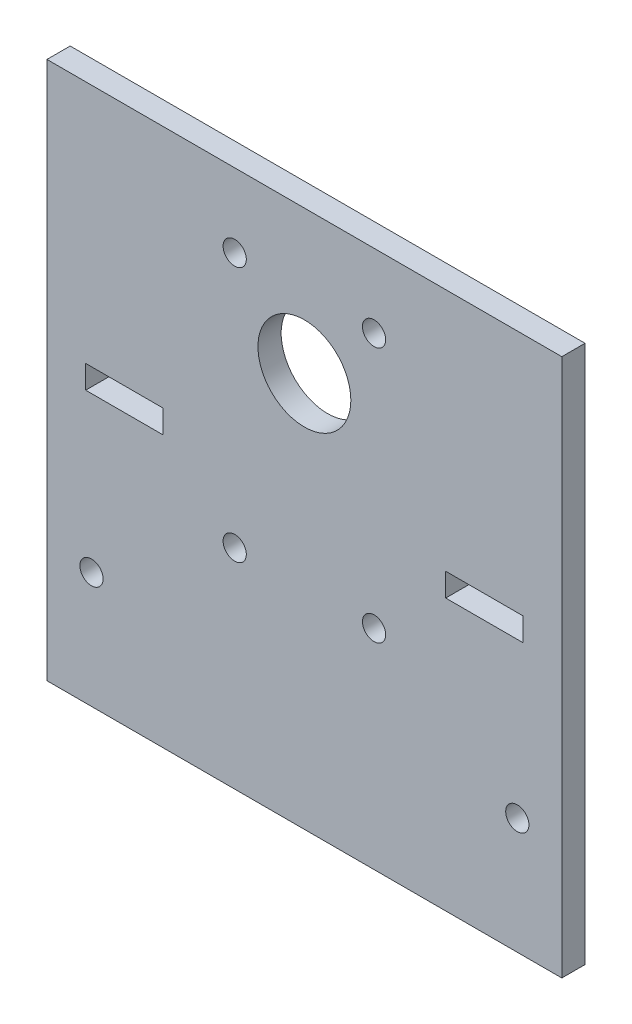
SolidWorks part; units mm, degrees
ref_plane "Front Plane" through (0, 0, 0) normal (0, 0, 1) x (1, 0, 0)
ref_plane "Top Plane" through (0, 0, 0) normal (0, 1, 0) x (1, 0, 0)
ref_plane "Right Plane" through (0, 0, 0) normal (1, 0, 0) x (0, 0, -1)
sketch "Sketch1" plane through (0, 0, 0) normal (0, 0, 1) x (1, 0, 0)
  line L1 (-33.25, 34.75) -> (33.25, 34.75)
  line L2 (-33.25, 34.75) -> (-33.25, -34.75)
  line L3 (-33.25, -34.75) -> (33.25, -34.75)
  line L4 (33.25, 34.75) -> (33.25, -34.75)
  line L5 (-33.25, 34.75) -> (33.25, -34.75) construction
  line L6 (-33.25, -34.75) -> (33.25, 34.75) construction
  point P0 (0, 0)
  dimension "D1" = 69.5
  dimension "D2" = 66.5
extrude "Boss-Extrude1" add sketch "Sketch1" along normal blind 3
sketch "Sketch3" plane through (0, 0, 3) normal (0, 0, 1) x (1, 0, 0)
  line L0 (33.25, 34.75) -> (-33.25, 34.75) construction
  line L1 (-33.25, 34.75) -> (-33.25, -34.75) construction
  line L3 (16, -14.75) -> (-16, -14.75) construction
  line L4 (16, -14.75) -> (16, 31.25) construction
  line L5 (16, 31.25) -> (-16, 31.25) construction
  line L6 (-16, -14.75) -> (-16, 31.25) construction
  circle A0 centre (0, 16.25) radius 6
  circle A1 centre (9, 25.25) radius 1.5
  circle A2 centre (-9, 25.25) radius 1.5
  circle A3 centre (9, -7.75) radius 1.5
  circle A4 centre (-9, -7.75) radius 1.5
  point P18 (0, -14.75)
  dimension "D1" = 12
  dimension "D8" = 3
  dimension "D11" = 3
  dimension "D16" = 3
  dimension "D19" = 3
  dimension "D2" = 18.5
  dimension "D3" = 33.25
  dimension "D4" = 15
  dimension "D5" = 32
  dimension "D6" = 46
  dimension "D7" = 16
  dimension "D9" = 6
  dimension "D10" = 7
  dimension "D12" = 7
  dimension "D13" = 6
  dimension "D14" = 7
  dimension "D15" = 7
  dimension "D17" = 7
  dimension "D18" = 7
extrude "Cut-Extrude1" cut sketch "Sketch3" against normal up to next
sketch "Sketch4" plane through (0, 0, 3) normal (0, 0, 1) x (1, 0, 0)
  line L0 (33.25, 34.75) -> (-33.25, 34.75) construction
  circle A0 centre (27.5, -19.75) radius 1.5
  point P6 (0, 34.75)
  dimension "D2" = 3
  dimension "D1" = 54.5
  dimension "D3" = 27.5
extrude "Cut-Extrude2" cut sketch "Sketch4" against normal up to next
mirror "Mirror1" about plane through (0, 0, 0) normal (1, 0, 0) of "Cut-Extrude2"
sketch "Sketch5" plane through (0, 0, 3) normal (0, 0, 1) x (1, 0, 0)
  line L0 (33.25, -34.75) -> (33.25, 34.75) construction
  line L1 (28.25, 0.25) -> (18.25, 0.25)
  line L2 (28.25, 0.25) -> (28.25, 3.25)
  line L3 (28.25, 3.25) -> (18.25, 3.25)
  line L4 (18.25, 0.25) -> (18.25, 3.25)
  line L5 (33.25, 34.75) -> (-33.25, 34.75) construction
  point P6 (33.25, 0)
  point P7 (23.25, 0.25)
  point P10 (0, 34.75)
  dimension "D1" = 10
  dimension "D2" = 3
  dimension "D3" = 5
  dimension "D4" = 34.5
extrude "Cut-Extrude3" cut sketch "Sketch5" against normal up to next
mirror "Mirror2" about plane through (0, 0, 0) normal (1, 0, 0) of "Cut-Extrude3"
